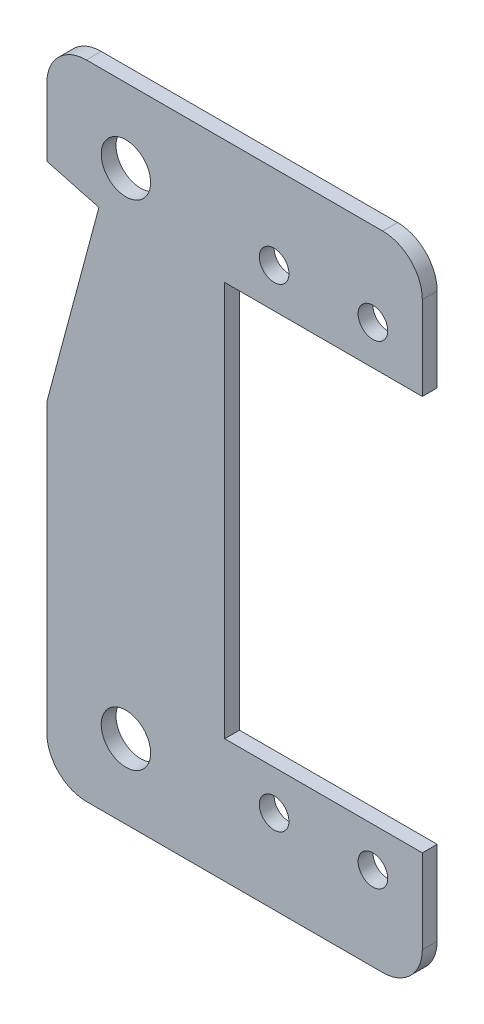
SolidWorks part; units mm, degrees
material "3.0205 (EN-AW 1200)"
ref_plane "Plan de face" through (0, 0, 0) normal (0, 0, 1) x (1, 0, 0)
ref_plane "Plan de dessus" through (0, 0, 0) normal (0, 1, 0) x (1, 0, 0)
ref_plane "Plan de droite" through (0, 0, 0) normal (1, 0, 0) x (0, 0, -1)
sketch "Esquisse1" plane through (0, 0, 0) normal (0, 0, 1) x (1, 0, 0)
  line L0 (38, -20) -> (38, -32.5)
  line L1 (38, 20) -> (18, 20)
  line L2 (28, 20) -> (28, -20) construction
  line L3 (38, -20) -> (18, -20)
  line L4 (18, 20) -> (18, -20)
  line L5 (38, 32.5) -> (0, 32.5)
  line L6 (38, 32.5) -> (38, 20)
  line L7 (38, -32.5) -> (0, -32.5)
  line L8 (0, 32.5) -> (0, -32.5)
  line L9 (0, 0) -> (28, 0) construction
  circle A0 centre (8, 25) radius 2.5
  circle A1 centre (23, 24) radius 1.5
  circle A2 centre (33, 24) radius 1.5
  circle A3 centre (33, -24) radius 1.5
  circle A4 centre (23, -24) radius 1.5
  circle A5 centre (8, -25) radius 2.5
  dimension "D1" = 10
  dimension "D2" = 3
  dimension "D3" = 48
  dimension "D6" = 10
  dimension "D7" = 8
  dimension "D8" = 7.5
  dimension "D10" = 5
  dimension "D4" = 40
  dimension "D5" = 20
  dimension "D9" = 12.5
extrude "Boss.-Extru.1" add sketch "Esquisse1" along normal blind 1.5
fillet "Congé1" radius 4 4 edges at (0, -32.5, 0.75) (38, -32.5, 0.75) (0, 32.5, 0.75) (38, 32.5, 0.75)
sketch "Esquisse2" plane through (0, 0, 1.5) normal (0, 0, 1) x (1, 0, 0)
  line L0 (0, 21.617) -> (5.2683, 20.2054)
  line L1 (0, 28.5) -> (0, -28.5) construction
  line L2 (5.2683, 20.2054) -> (0, 0.5437)
  line L3 (0, 0.5437) -> (0, 21.617)
  line L4 (-23.2265, 27.8405) -> (5.2683, 20.2054) construction
  line L5 (5.2683, 20.2054) -> (-11.8137, -43.5457) construction
extrude "Enlèv. mat.-Extru.1" cut sketch "Esquisse2" against normal through all
